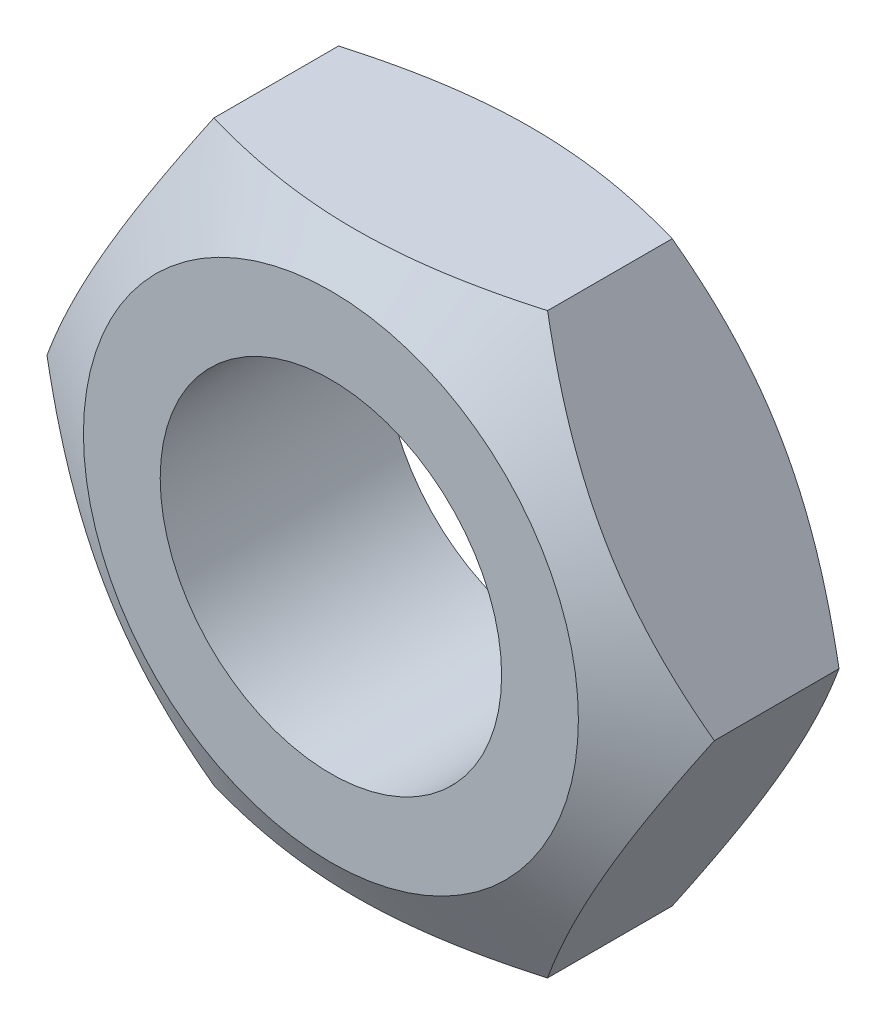
SolidWorks part; units mm, degrees
ref_plane "Front Plane" through (0, 0, 0) normal (0, 0, 1) x (1, 0, 0)
ref_plane "Top Plane" through (0, 0, 0) normal (0, 1, 0) x (1, 0, 0)
ref_plane "Right Plane" through (0, 0, 0) normal (1, 0, 0) x (0, 0, -1)
sketch "Sketch1" plane through (0, 0, 0) normal (0, 0, 1) x (1, 0, 0)
  line L2 (4.1216, 7.1374) -> (-4.1204, 7.1381)
  line L3 (-4.1204, 7.1381) -> (-8.242, 0.0007)
  line L4 (-8.242, 0.0007) -> (-4.1216, -7.1374)
  line L5 (-4.1216, -7.1374) -> (4.1204, -7.1381)
  line L6 (4.1204, -7.1381) -> (8.242, -0.0007)
  line L7 (8.242, -0.0007) -> (4.1216, 7.1374)
  circle A0 centre (0, 0) radius 4.7625
extrude "Boss-Extrude1" add sketch "Sketch1" along normal blind 5.5372 contours L3 L4 L5 L6 L7 L2
sketch "Sketch6" plane through (0, 0, 0) normal (0, 0, -1) x (-1, 0, 0)
  circle A0 centre (0, 0) radius 6.1127
extrude "Cut-Extrude4" cut sketch "Sketch6" along direction (0, 0, 1) on the side against the normal through all draft 60 flip side to cut
ref_plane "Plane2" through (0, 0, 2.7686) normal (0, 0, 1) x (1, 0, 0)
mirror "Mirror1" about plane through (0, 0, 2.7686) normal (0, 0, 1) of "Cut-Extrude4"
hole_wizard "3/8-24 Tapped Hole1" positions "Sketch8" profile "Sketch7" tap size "3/8-24" standard "ANSI Inch"
sketch "Sketch8" plane through (0, 0, 5.5372) normal (0, 0, 1) x (1, 0, 0)
  point P0 (0, 0)
sketch "Sketch7" plane through (0, 0, 5.5372) normal (1, 0, 0) x (0, -1, 0)
  line L0 (0, 0) -> (0, 26.9175)
  line L1 (0, 26.9175) -> (4.2164, 24.384)
  line L2 (4.2164, 24.384) -> (4.2164, 0)
  line L5 (4.2164, 0) -> (0, 0)
  line L10 (0, 26.9175) -> (-4.2164, 24.384) construction
  line L11 (0, -6.35) -> (0, 107.95) construction
  dimension "Tap Drill Dia." = 8.4328
  dimension "Tap Drill Depth" = 24.384
  dimension "Drill Angle" = 118
cosmetic thread "Hole Thread1" parameters "D1"=5.5372, "D2"=9.525
